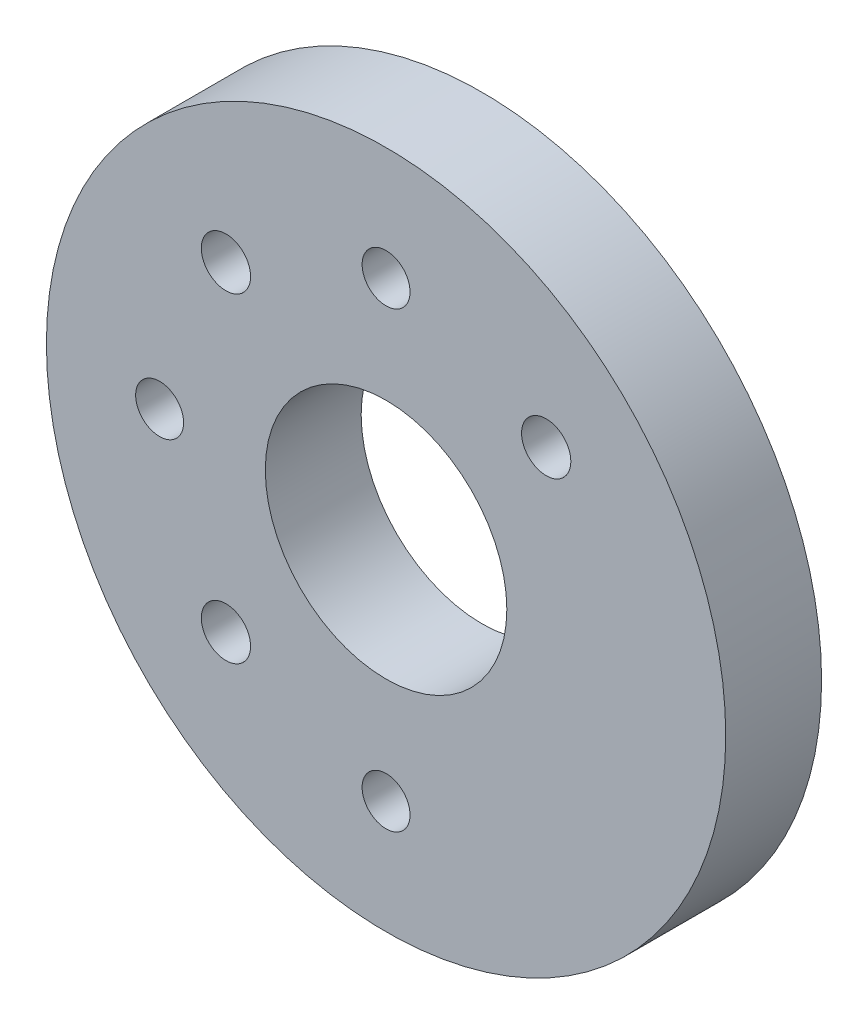
SolidWorks part; units mm, degrees
ref_plane "Front Plane" through (0, 0, 0) normal (0, 0, 1) x (1, 0, 0)
ref_plane "Top Plane" through (0, 0, 0) normal (0, 1, 0) x (1, 0, 0)
ref_plane "Right Plane" through (0, 0, 0) normal (1, 0, 0) x (0, 0, -1)
sketch "Sketch1" plane through (0, 0, 0) normal (0, 0, 1) x (1, 0, 0)
  line L0 (-31.5971, 0) -> (0, 0) construction
  line L1 (0, 0) -> (-23.1382, 23.1382) construction
  circle A0 centre (0, 0) radius 22.5
  circle A1 centre (0, 0) radius 8
  circle A2 centre (0, 0) radius 15 construction
  circle A3 centre (0, 15) radius 1.5875
  circle A4 centre (15, 0) radius 1.5875 construction
  circle A5 centre (0, -15) radius 1.5875
  circle A6 centre (-15, 0) radius 1.5875
  circle A7 centre (-10.6066, 10.6066) radius 1.632
  circle A8 centre (10.6066, 10.6066) radius 1.632
  circle A9 centre (10.6066, -10.6066) radius 1.632 construction
  circle A10 centre (-10.6066, -10.6066) radius 1.632
  point P24 (0, 0)
  point P27 (0, 0)
  dimension "D1" = 45
  dimension "D2" = 16
  dimension "D3" = 30
  dimension "D4" = 3.175
  dimension "D8" = 3.2639
  dimension "D6" = 45
  dimension "D5" = 4
  dimension "D7" = 4
extrude "Boss-Extrude1" add sketch "Sketch1" along normal blind 6.35
